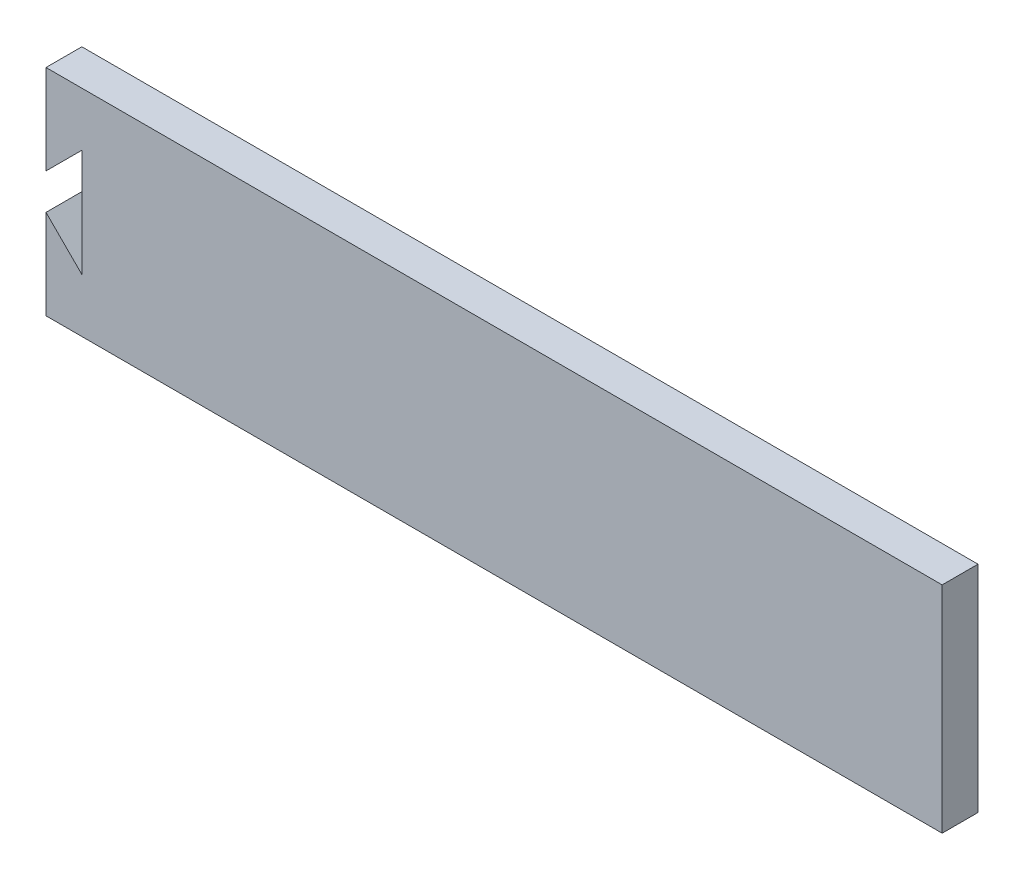
SolidWorks part; units mm, degrees
ref_plane "前视基准面" through (0, 0, 0) normal (0, 0, 1) x (1, 0, 0)
ref_plane "上视基准面" through (0, 0, 0) normal (0, 1, 0) x (1, 0, 0)
ref_plane "右视基准面" through (0, 0, 0) normal (1, 0, 0) x (0, 0, -1)
sketch "草图1" plane through (0, 0, 0) normal (0, 0, 1) x (1, 0, 0)
  line L0 (-142.9273, 66.0609) -> (107.0727, 66.0609)
  line L1 (-142.9273, 66.0609) -> (-142.9273, 6.0609)
  line L2 (107.0727, 66.0609) -> (107.0727, 6.0609)
  line L3 (-142.9273, 6.0609) -> (107.0727, 6.0609)
  dimension "D1" = 250
  dimension "D2" = 60
extrude "凸台-拉伸1" add sketch "草图1" along normal blind 10
sketch "草图8" plane through (-142.9273, 0, 0) normal (-1, 0, 0) x (0, 0, 1)
  line L0 (0, 41.0609) -> (10, 41.0609)
  line L1 (0, 41.0609) -> (0, 31.0609)
  line L2 (10, 41.0609) -> (10, 31.0609)
  line L3 (0, 31.0609) -> (10, 31.0609)
  line L4 (0, 66.0609) -> (0, 6.0609) construction
  line L5 (10, 66.0609) -> (10, 6.0609) construction
  line L6 (10, 66.0609) -> (0, 66.0609) construction
  line L7 (10, 6.0609) -> (0, 6.0609) construction
  dimension "D1" = 25
  dimension "D2" = 25
extrude "切除-拉伸3" cut sketch "草图8" against normal blind 10
sketch "草图9" plane through (0, 0, 10) normal (0, 0, 1) x (1, 0, 0)
  line L0 (-142.9273, 41.0609) -> (-132.9273, 51.0609)
  line L1 (-132.9273, 51.0609) -> (-132.9273, 41.0609)
  line L2 (-132.9273, 41.0609) -> (-142.9273, 41.0609)
  dimension "D1" = 45
extrude "切除-拉伸4" cut sketch "草图9" against normal blind 10
sketch "草图10" plane through (0, 0, 10) normal (0, 0, 1) x (1, 0, 0)
  line L0 (-142.9273, 31.0609) -> (-132.9273, 21.0609)
  line L1 (-132.9273, 21.0609) -> (-132.9273, 31.0609)
  line L2 (-132.9273, 31.0609) -> (-142.9273, 31.0609)
  dimension "D1" = 45
extrude "切除-拉伸5" cut sketch "草图10" against normal blind 10
